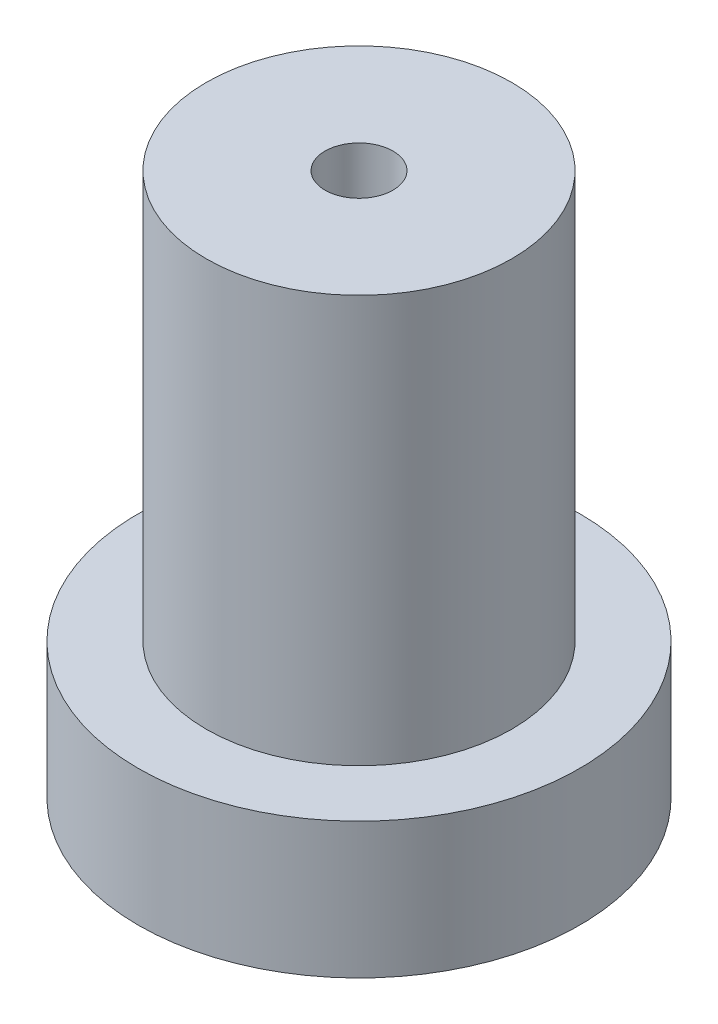
SolidWorks part; units mm, degrees
ref_plane "Front Plane" through (0, 0, 0) normal (0, 0, 1) x (1, 0, 0)
ref_plane "Top Plane" through (0, 0, 0) normal (0, 1, 0) x (1, 0, 0)
ref_plane "Right Plane" through (0, 0, 0) normal (1, 0, 0) x (0, 0, -1)
sketch "Sketch1" plane through (0, 0, 0) normal (0, 0, 1) x (1, 0, 0)
  line L0 (0, -8.8206) -> (0, 31.0973) construction
  line L3 (0, -2) -> (6.5, -2)
  line L4 (6.5, 2) -> (6.5, -2)
  line L7 (0, 14) -> (4.5, 14)
  line L10 (4.5, 14) -> (4.5, 2)
  line L13 (4.5, 2) -> (6.5, 2)
  line L14 (0, 14) -> (0, -2)
  point P0 (0, 0)
  point P6 (0, 8)
  dimension "D1" = 4.5
  dimension "D2" = 16
  dimension "D4" = 12
  dimension "D5" = 2
  dimension "D6" = 6.5
revolve "Revolve1" add sketch "Sketch1" angle 360 about L14
sketch "Sketch2" plane through (0, -2, 0) normal (0, -1, 0) x (1, 0, 0)
  circle A0 centre (0, 0) radius 1
extrude "Cut-Extrude1" cut sketch "Sketch2" against normal through all
